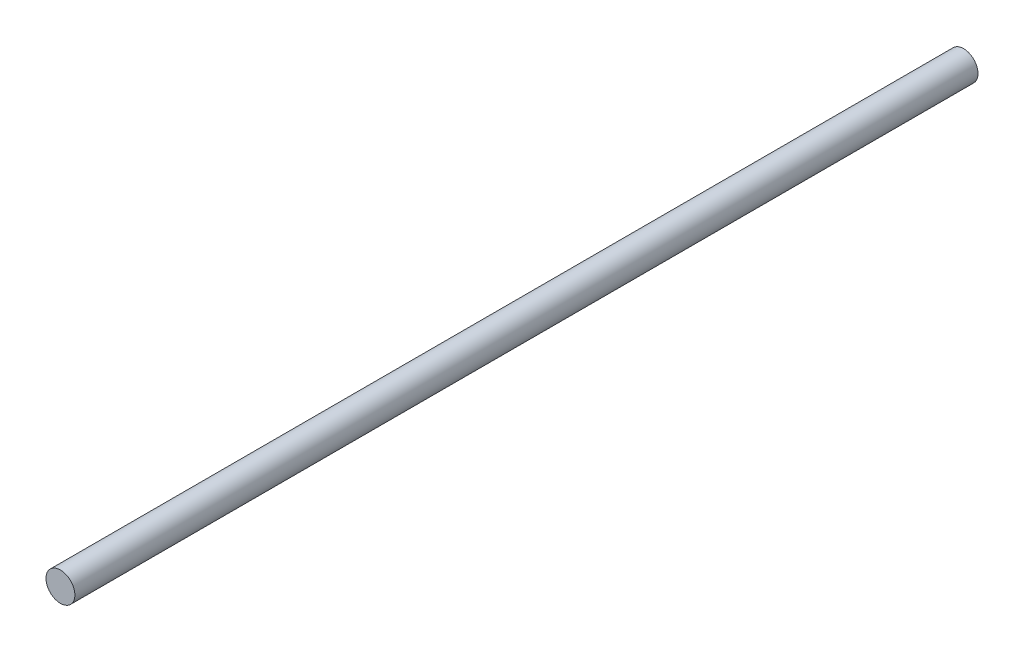
SolidWorks part; units mm, degrees
ref_plane "Спереди" through (0, 0, 0) normal (0, 0, 1) x (1, 0, 0)
ref_plane "Сверху" through (0, 0, 0) normal (0, 1, 0) x (1, 0, 0)
ref_plane "Справа" through (0, 0, 0) normal (1, 0, 0) x (0, 0, -1)
sketch "Эскиз1" plane through (0, 0, 0) normal (0, 0, 1) x (1, 0, 0)
  circle A0 centre (0, 0) radius 6
  dimension "D1" = 12
extrude "Бобышка-Вытянуть1" add sketch "Эскиз1" along normal blind 375
